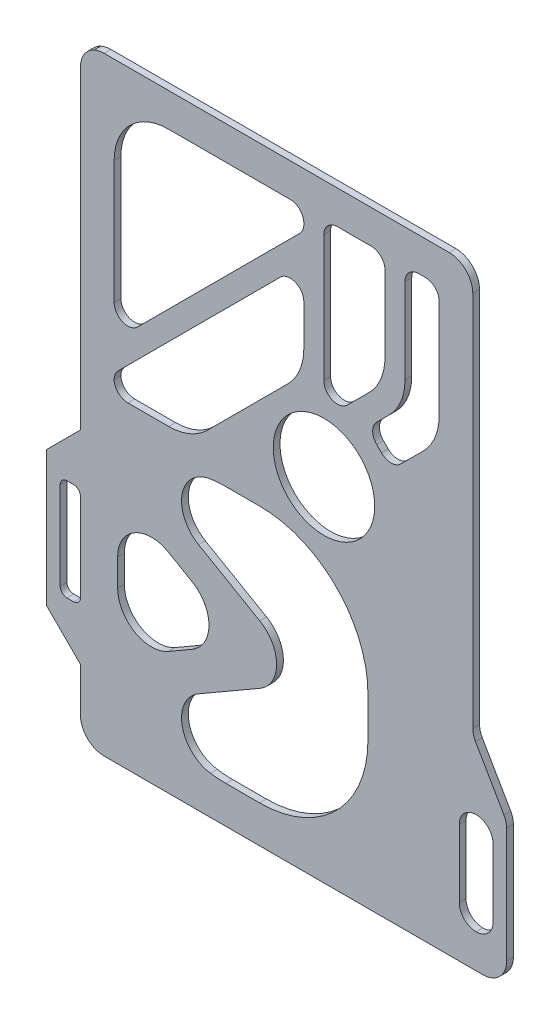
SolidWorks part; units mm, degrees
ref_plane "前视基准面" through (0, 0, 0) normal (0, 0, 1) x (1, 0, 0)
ref_plane "上视基准面" through (0, 0, 0) normal (0, 1, 0) x (1, 0, 0)
ref_plane "右视基准面" through (0, 0, 0) normal (1, 0, 0) x (0, 0, -1)
sketch "草图1" plane through (0, 0, 0) normal (0, 0, 1) x (1, 0, 0)
  line L27 (-1, -50) -> (-1.032, -50)
  line L28 (-34, 37.6372) -> (-34, 37.6623)
  line L29 (-36, 34.5) -> (-36, -12)
  line L30 (-36, -12) -> (-41, -17)
  line L31 (-41, -17) -> (-41, -37)
  line L32 (-41, -37) -> (-36, -42)
  line L33 (-36, -42) -> (-36, -48.5)
  line L34 (-32.5, -52) -> (-3, -52)
  line L35 (-38, -34.5) -> (-37, -34.5)
  line L36 (-36, -33.5) -> (-36, -20.5)
  line L37 (-37, -19.5) -> (-38, -19.5)
  line L38 (-39, -20.5) -> (-39, -33.5)
  line L40 (22, 37.9774) -> (-32.5, 37.9774)
  line L46 (-14.5, -46.5) -> (-9.5, -46.5)
  line L47 (-30.5, -24.5) -> (-30.5, -30.5)
  line L48 (-9.5, -8.5) -> (-14.5, -8.5)
  line L49 (6.5, -30.5) -> (6.5, -24.5)
  line L50 (11.9774, 31) -> (11.9774, 18.3848)
  line L51 (15, 33.0226) -> (14, 33.0226)
  line L52 (17.0226, 16.3137) -> (17.0226, 31)
  line L53 (11.3592, 7.3271) -> (14.6729, 10.6408)
  line L54 (7.7916, 8.0342) -> (8.4987, 7.3271)
  line L55 (9.6408, 12.7439) -> (7.7916, 10.8947)
  line L56 (7, 33.0226) -> (2, 33.0226)
  line L57 (9.0226, 19.8137) -> (9.0226, 31)
  line L58 (3.4302, 10.8982) -> (6.6729, 14.1408)
  line L59 (-0.0226, 31) -> (-0.0226, 12.3284)
  line L60 (-6.4302, 22.3592) -> (-30.4302, -1.6408)
  line L61 (-2.9774, 14.9289) -> (-2.9774, 20.9289)
  line L62 (-17.2561, -2.6729) -> (-5.3271, 9.2561)
  line L63 (-29, -5.0226) -> (-22.9289, -5.0226)
  line L64 (-27.5698, 5.3982) -> (-3.5698, 29.3982)
  line L65 (-31.0226, 25) -> (-31.0226, 6.8284)
  line L66 (-5, 33.0226) -> (-23, 33.0226)
  line L67 (-2.9774, 30.8284) -> (-2.9774, 31)
  line L69 (22, -2) -> (22, -22)
  line L70 (22, -22) -> (27, -30.6603)
  line L71 (27, -30.6603) -> (27, -52)
  line L72 (27, -52) -> (-3, -52)
  line L73 (22, 37.9774) -> (22, -2)
  arc A13 (-34, 37.6623) -> (-36, 34.5) centre (-32.5, 34.5) ccw
  arc A14 (-36, -48.5) -> (-32.5, -52) centre (-32.5, -48.5) ccw
  circle A15 centre (0, 0) radius 7.5
  arc A16 (-39, -33.5) -> (-38, -34.5) centre (-38, -33.5) ccw
  arc A17 (-37, -34.5) -> (-36, -33.5) centre (-37, -33.5) ccw
  arc A18 (-36, -20.5) -> (-37, -19.5) centre (-37, -20.5) ccw
  arc A19 (-38, -19.5) -> (-39, -20.5) centre (-38, -20.5) ccw
  arc A21 (-32.5, 37.9774) -> (-34, 37.6372) centre (-32.5, 34.5) ccw
  arc A24 (-30.5, -30.5) -> (-14.5, -46.5) centre (-14.5, -30.5) ccw
  arc A25 (-14.5, -8.5) -> (-30.5, -24.5) centre (-14.5, -24.5) ccw
  arc A26 (6.5, -24.5) -> (-9.5, -8.5) centre (-9.5, -24.5) ccw
  arc A27 (-9.5, -46.5) -> (6.5, -30.5) centre (-9.5, -30.5) ccw
  arc A28 (14, 33.0226) -> (11.9774, 31) centre (14, 31) ccw
  arc A29 (17.0226, 31) -> (15, 33.0226) centre (15, 31) ccw
  arc A30 (14.6729, 10.6408) -> (17.0226, 16.3137) centre (9, 16.3137) ccw
  arc A31 (8.4987, 7.3271) -> (11.3592, 7.3271) centre (9.9289, 8.7574) ccw
  arc A32 (7.7916, 10.8947) -> (7.7916, 8.0342) centre (9.2218, 9.4645) ccw
  arc A33 (9.6408, 12.7439) -> (11.9774, 18.3848) centre (4, 18.3848) ccw
  arc A34 (9.0226, 31) -> (7, 33.0226) centre (7, 31) ccw
  arc A35 (6.6729, 14.1408) -> (9.0226, 19.8137) centre (1, 19.8137) ccw
  arc A36 (-0.0226, 12.3284) -> (3.4302, 10.8982) centre (2, 12.3284) ccw
  arc A37 (2, 33.0226) -> (-0.0226, 31) centre (2, 31) ccw
  arc A38 (-2.9774, 20.9289) -> (-6.4302, 22.3592) centre (-5, 20.9289) ccw
  arc A39 (-5.3271, 9.2561) -> (-2.9774, 14.9289) centre (-11, 14.9289) ccw
  arc A40 (-22.9289, -5.0226) -> (-17.2561, -2.6729) centre (-22.9289, 3) ccw
  arc A41 (-31.0223, -3.0355) -> (-29, -5.0226) centre (-29, -3) ccw
  arc A42 (-30.4302, -1.6408) -> (-31.0223, -3.0355) centre (-29, -3.0711) ccw
  arc A43 (-31.0226, 6.8284) -> (-27.5698, 5.3982) centre (-29, 6.8284) ccw
  arc A44 (-23, 33.0226) -> (-31.0226, 25) centre (-23, 25) ccw
  arc A45 (-2.9774, 31) -> (-5, 33.0226) centre (-5, 31) ccw
  arc A46 (-3.5698, 29.3982) -> (-2.9774, 30.8284) centre (-5, 30.8284) ccw
  dimension "D3" = 5
  dimension "D1" = 58
  dimension "D2" = 150
  dimension "D4" = 30
  dimension "D6" = 50
extrude "凸台-拉伸1" add sketch "草图1" along normal blind 1
fillet "圆角1" radius 3 2 edges at (27, -30.6603, 0.5) (22, -22, 0.5)
fillet "圆角2" radius 3.5 2 edges at (27, -52, 0.5) (22, 37.9774, 0.5)
sketch "草图2" plane through (0, 0, 0) normal (0, 0, -1) x (-1, 0, 0)
  line L0 (32.5, -52) -> (-23.5, -52) construction
  line L1 (-22.51, -47) -> (-22.49, -47)
  line L2 (-25, -44.51) -> (-25, -34.49)
  line L3 (-22.51, -32) -> (-22.49, -32)
  line L4 (-20, -44.51) -> (-20, -34.49)
  line L5 (-27, -31.4641) -> (-27, -48.5) construction
  arc A0 (-25, -44.51) -> (-22.51, -47) centre (-22.51, -44.51) ccw
  arc A1 (-22.49, -47) -> (-20, -44.51) centre (-22.49, -44.51) ccw
  arc A2 (-20, -34.49) -> (-22.49, -32) centre (-22.49, -34.49) ccw
  arc A3 (-22.51, -32) -> (-25, -34.49) centre (-22.51, -34.49) ccw
  point P10 (-25, -47)
  point P13 (-20, -47)
  point P16 (-20, -32)
  dimension "D5" = 2.49
  dimension "D1" = 5
  dimension "D2" = 15
  dimension "D3" = 5
  dimension "D4" = 2
extrude "切除-拉伸1" cut sketch "草图2" against normal blind 10
sketch "草图3" plane through (0, 0, 0) normal (0, 0, -1) x (-1, 0, 0)
  line L0 (12, -27.5) -> (29.3205, -17.5)
  line L1 (12, -27.5) -> (29.3205, -37.5)
  line L2 (2, -27.5) -> (30.7132, -10.9224)
  line L3 (2, -27.5) -> (30.7132, -44.0776)
  line L4 (-6.5, -27.5) -> (30.5, -27.5) construction
  line L5 (-6.5, -30.5) -> (-6.5, -24.5) construction
  line L6 (30.5, -24.5) -> (30.5, -30.5) construction
  line L7 (12, -8.5) -> (12, -46.5) construction
  line L8 (9.5, -8.5) -> (14.5, -8.5) construction
  line L9 (14.5, -46.5) -> (9.5, -46.5) construction
  line L10 (30.7132, -10.9224) -> (30.7132, -20.442)
  line L11 (30.7132, -34.558) -> (30.7132, -44.0776)
  arc A0 (29.3205, -37.5) -> (30.7132, -34.558) centre (12, -27.5) ccw
  arc A2 (30.7132, -20.442) -> (29.3205, -17.5) centre (12, -27.5) ccw
  dimension "D2" = 40
  dimension "D1" = 60
extrude "凸台-拉伸2" add sketch "草图3" against normal blind 1
fillet "圆角3" radius 5 6 edges at (-26.1647, -41.4515, 0.5) (-28.9812, -37.3041, 0.5) (-28.9812, -17.6959, 0.5) (-26.1647, -13.5485, 0.5) (-12, -27.5, 0.5) (-2, -27.5, 0.5)
